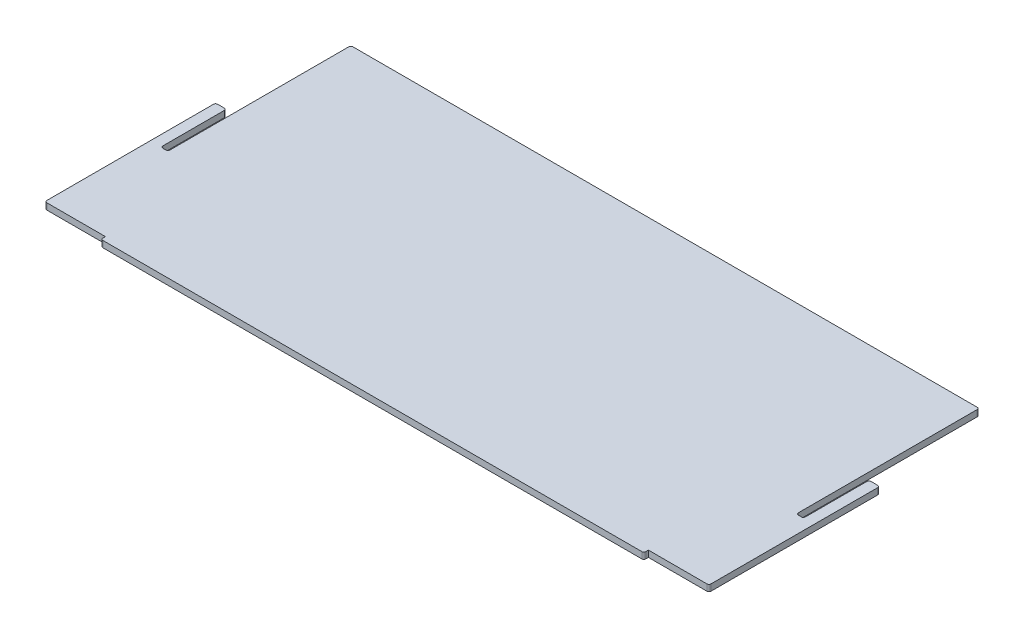
SolidWorks part; units mm, degrees
material "Alloy Steel"
ref_plane "X-Y Datum" through (0, 0, 0) normal (0, 0, 1) x (1, 0, 0)
ref_plane "X-Z Datum" through (0, 0, 0) normal (0, 1, 0) x (1, 0, 0)
ref_plane "Y-Z Datum" through (0, 0, 0) normal (1, 0, 0) x (0, 0, -1)
sketch "Sketch1" plane through (0, 0, 0) normal (0, 1, 0) x (1, 0, 0)
  line L0 (292.0733, 0) -> (313.3674, 0)
  line L1 (0, 0) -> (21.2941, 0)
  line L2 (0, 0) -> (0, 143.6878)
  line L3 (0, 143.6878) -> (313.3674, 143.6878)
  line L4 (313.3674, 0) -> (313.3674, 143.6878)
  line L5 (21.2941, -2.286) -> (292.0733, -2.286)
  line L6 (21.2941, -2.286) -> (21.2941, 0)
  line L8 (292.0733, -2.286) -> (292.0733, 0)
  line L9 (21.2941, -2.286) -> (156.6837, 0) construction
  line L10 (156.6837, 0) -> (292.0733, -2.286) construction
  point P5 (156.6837, 0)
extrude "Boss-Extrude1" add sketch "Sketch1" along normal blind 3.175
sketch "Sketch2" plane through (0, 3.175, 0) normal (0, 1, 0) x (1, 0, 0)
  line L0 (0, 0) -> (-8.9267, 0)
  line L1 (-8.9267, 0) -> (-8.9267, 85.153)
  line L4 (0, 52.4798) -> (-3.556, 52.4798)
  line L5 (-3.556, 85.153) -> (-3.556, 52.4798)
  line L6 (-8.9267, 85.153) -> (-3.556, 85.153)
  line L7 (0, 52.4798) -> (0, 0)
  line L8 (156.6837, -2.286) -> (156.6837, 36.534) construction
  line L9 (21.2941, -2.286) -> (292.0733, -2.286) construction
  line L10 (313.3674, 52.4798) -> (316.9234, 52.4798)
  line L11 (316.9234, 85.153) -> (316.9234, 52.4798)
  line L12 (322.2941, 85.153) -> (316.9234, 85.153)
  line L13 (322.2941, 0) -> (322.2941, 85.153)
  line L14 (313.3674, 0) -> (322.2941, 0)
  line L15 (313.3674, 52.4798) -> (313.3674, 0)
extrude "Boss-Extrude2" add sketch "Sketch2" against normal through all
fillet "Fillet1" radius 1 14 edges at (0, 1.5875, -143.6878) (313.3674, 1.5875, -143.6878) (316.9234, 1.5875, -52.4798) (313.3674, 1.5875, -52.4798) (316.9234, 1.5875, -85.153) (322.2941, 1.5875, -85.153) (322.2941, 1.5875, 0) (292.0733, 1.5875, 2.286) (21.2941, 1.5875, 2.286) (-8.9267, 1.5875, 0) (0, 1.5875, -52.4798) (-3.556, 1.5875, -52.4798) (-3.556, 1.5875, -85.153) (-8.9267, 1.5875, -85.153)
